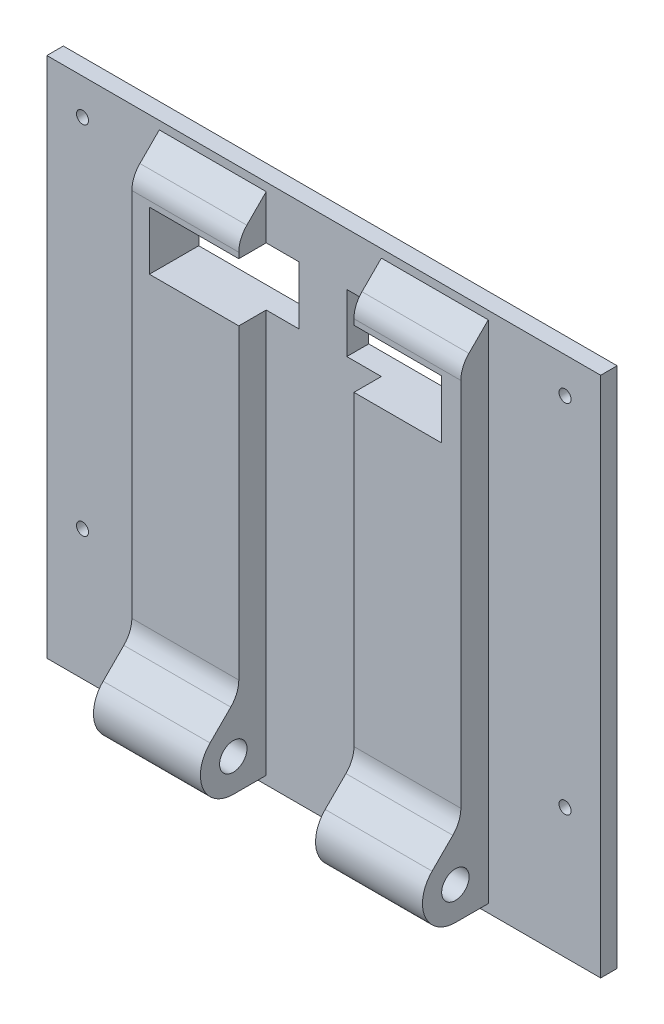
SolidWorks part; units mm, degrees
ref_plane "Front Plane" through (0, 0, 0) normal (0, 0, 1) x (1, 0, 0)
ref_plane "Top Plane" through (0, 0, 0) normal (0, 1, 0) x (1, 0, 0)
ref_plane "Right Plane" through (0, 0, 0) normal (1, 0, 0) x (0, 0, -1)
sketch "Sketch1" plane through (0, 0, 0) normal (0, 0, 1) x (1, 0, 0)
  line L1 (0, 43.6) -> (0, 0) construction
  line L2 (0, 0) -> (0, -43.6) construction
  line L3 (-46.5, 0) -> (0, 0) construction
  line L4 (0, 0) -> (46.5, 0) construction
  line L5 (46.5, 43.6) -> (46.5, -43.6) construction
  line L6 (-44, 41.1) -> (-44, -23.9) construction
  line L7 (-44, -23.9) -> (44, -23.9) construction
  line L8 (44, -23.9) -> (44, 41.1) construction
  line L9 (44, 41.1) -> (-44, 41.1) construction
  line L10 (50.5, 47.6) -> (-50.5, 47.6)
  line L11 (50.5, 47.6) -> (50.5, -47.6)
  line L12 (50.5, -47.6) -> (-50.5, -47.6)
  line L13 (-50.5, 47.6) -> (-50.5, -47.6)
  line L16 (49, -4.7) -> (49, 21.4) construction
  line L17 (49, 21.4) -> (46.5, 21.4) construction
  line L18 (46.5, 21.4) -> (46.5, 43.6) construction
  line L19 (46.5, 43.6) -> (-46.5, 43.6) construction
  line L20 (-46.5, 43.6) -> (-46.5, -43.6) construction
  line L21 (-46.5, -43.6) -> (46.5, -43.6) construction
  line L22 (46.5, -43.6) -> (46.5, -4.7) construction
  line L23 (46.5, -4.7) -> (49, -4.7) construction
  line L25 (-26.8, 38) -> (-26.8, 27.4)
  line L26 (-4.5, 38) -> (-26.8, 38)
  line L27 (-4.5, 27.4) -> (-4.5, 38)
  line L28 (-26.8, 27.4) -> (-4.5, 27.4)
  line L33 (4.2, 38) -> (4.2, 27.4)
  line L34 (26.5, 38) -> (4.2, 38)
  line L35 (26.5, 27.4) -> (26.5, 38)
  line L36 (4.2, 27.4) -> (26.5, 27.4)
  circle A4 centre (44, 41.1) radius 1.1
  circle A5 centre (44, -23.9) radius 1.1
  circle A6 centre (-44, 41.1) radius 1.1
  circle A7 centre (-44, -23.9) radius 1.1
  point P36 (-4.5, 32.7)
  dimension "D11" = 2.2
  dimension "D1" = 87.2
  dimension "D2" = 93
  dimension "D3" = 2.5
  dimension "D4" = 38.9
  dimension "D5" = 26.1
  dimension "D6" = 10.6
  dimension "D7" = 5.6
  dimension "D8" = 4.5
  dimension "D9" = 4.2
  dimension "D10" = 22.3
  dimension "D12" = 2.5
  dimension "D13" = 65
  dimension "D14" = 88
  dimension "D15" = 2.5
  dimension "D16" = 50.5
  dimension "D17" = 101
  dimension "D18" = 95.2
  dimension "D19" = 47.6
extrude "Boss-Extrude1" add sketch "Sketch1" along normal blind 3
sketch "Sketch2" [suppressed] plane through (0, 0, 3) normal (0, 0, 1) x (1, 0, 0)
  line L0 (46.5, 46.1) -> (-46.5, 46.1)
  line L1 (-49, 43.6) -> (-49, -43.6)
  line L2 (-46.5, -46.1) -> (46.5, -46.1)
  line L3 (49, -43.6) -> (49, -7.2)
  line L7 (49, 23.9) -> (49, 43.6)
  line L8 (50.5, -47.6) -> (50.5, 47.6) construction
  line L9 (-50.5, -47.6) -> (50.5, -47.6) construction
  line L16 (46.5, -4.7) -> (49, -4.7)
  line L18 (49, 21.4) -> (46.5, 21.4)
  line L19 (46.5, 21.4) -> (46.5, 43.6)
  line L20 (46.5, 43.6) -> (-46.5, 43.6)
  line L21 (-46.5, 43.6) -> (-46.5, -43.6)
  line L22 (-46.5, -43.6) -> (46.5, -43.6)
  line L23 (46.5, -43.6) -> (46.5, -4.7)
  line L24 (-49, -46.1) -> (49, -46.1) construction
  line L25 (49, -46.1) -> (49, -7.2) construction
  line L26 (-49, 46.1) -> (-49, -46.1) construction
  line L27 (49, 23.9) -> (49, 46.1) construction
  line L28 (49, 46.1) -> (-49, 46.1) construction
  line L29 (49, 23.9) -> (49, 21.4)
  line L30 (49, -4.7) -> (49, -7.2)
  line L31 (51.5, 23.9) -> (49, 23.9) construction
  line L32 (51.5, -7.2) -> (51.5, 23.9) construction
  line L33 (49, -7.2) -> (51.5, -7.2) construction
  line L41 (49, -4.7) -> (49, 21.4) construction
  arc A0 (46.5, -46.1) -> (49, -43.6) centre (46.5, -43.6) ccw
  arc A1 (-49, -43.6) -> (-46.5, -46.1) centre (-46.5, -43.6) ccw
  arc A2 (49, 43.6) -> (46.5, 46.1) centre (46.5, 43.6) ccw
  arc A3 (-49, 43.6) -> (-46.5, 46.1) centre (-46.5, 43.6) cw
  dimension "D3" = 2.5
  dimension "D1" = 97
  dimension "D2" = 87.2
  dimension "D4" = 4
sketch "Sketch4" plane through (0, 0, 3) normal (0, 0, 1) x (1, 0, 0)
  line L0 (0, 46.1) -> (0, -46.1) construction
  line L3 (50.5, 47.6) -> (-50.5, 47.6) construction
  line L5 (-50.5, -47.6) -> (50.5, -47.6) construction
  line L6 (-50.5, 47.6) -> (-50.5, -47.6) construction
  point P8 (0, 0)
  dimension "D1" = 1.5
  dimension "D2" = 1.5
  dimension "D3" = 50.5
ref_plane "Plane1" through (0, 0, 0) normal (-1, 0, 0) x (0, -1, 0)
sketch "Sketch5" plane through (0, 0, 0) normal (-1, 0, 0) x (0, -1, 0)
  line L0 (-46.1, 3) -> (46.1, 3) construction
  line L1 (46.1, 9) -> (46.1, 3) construction
  line L2 (46.1, 9) -> (46.1, 3)
  line L3 (46.1, 3) -> (25.6147, 3)
  line L4 (32.0792, 9.4645) -> (35.8574, 13.2426)
  line L5 (25.6147, 3) -> (-46.1, 3)
  line L6 (-46.1, 3) -> (-42.5645, 6.5355)
  line L7 (-39.0289, 8) -> (28.5437, 8)
  line L8 (25.6147, 3) -> (30.6147, 8) construction
  line L10 (47.6, 3) -> (47.6, 0) construction
  circle A2 centre (40.1, 9) radius 2.5
  arc A3 (46.1, 9) -> (35.8574, 13.2426) centre (40.1, 9) ccw
  arc A4 (28.5437, 8) -> (32.0792, 9.4645) centre (28.5437, 13) ccw
  arc A5 (-42.5645, 6.5355) -> (-39.0289, 8) centre (-39.0289, 3) cw
  arc A6 (35.8574, 13.2426) -> (40.1, 3) centre (40.1, 9) ccw construction
  arc A7 (40.1, 3) -> (46.1, 9) centre (40.1, 9) ccw construction
  dimension "D1" = 5
  dimension "D2" = 12
  dimension "D5" = 5
  dimension "D3" = 45
  dimension "D4" = 5
  dimension "D6" = 1.5
  dimension "D7" = 1.5
  dimension "D8" = 20.4853
extrude "Boss-Extrude3" add sketch "Sketch5" along normal blind 30 and the other way blind 30
sketch "Sketch7" plane through (-30, 0, 0) normal (-1, 0, 0) x (0, 0, 1)
  line L6 (3, 46.1) -> (3, -46.1)
  line L7 (3, 46.1) -> (3, -46.1)
  line L8 (13.2426, -35.8574) -> (9.4645, -32.0792)
  line L9 (8, -28.5437) -> (8, 39.0289)
  line L15 (6.5355, 42.5645) -> (3, 46.1)
  line L17 (3, -46.1) -> (9, -46.1)
  line L18 (13.2426, -35.8574) -> (9.4645, -32.0792)
  line L19 (8, -28.5437) -> (8, 39.0289)
  line L20 (6.5355, 42.5645) -> (3, 46.1)
  line L22 (3, -46.1) -> (9, -46.1)
  arc A3 (9, -46.1) -> (13.2426, -35.8574) centre (9, -40.1) ccw
  arc A4 (8, -28.5437) -> (9.4645, -32.0792) centre (13, -28.5437) ccw
  arc A5 (8, 39.0289) -> (6.5355, 42.5645) centre (3, 39.0289) ccw
  arc A9 (9, -46.1) -> (13.2426, -35.8574) centre (9, -40.1) ccw
  arc A10 (8, -28.5437) -> (9.4645, -32.0792) centre (13, -28.5437) ccw
  arc A11 (8, 39.0289) -> (6.5355, 42.5645) centre (3, 39.0289) ccw
  dimension "D1" = 0
extrude "Cut-Extrude1" cut sketch "Sketch7" against normal blind 21 from offset 19.5 offset against normal yes
sketch "Sketch8" plane through (-30, 0, 0) normal (-1, 0, 0) x (0, 0, 1)
  line L0 (9.4645, -32.0792) -> (3, -25.6147)
  line L1 (13.2426, -35.8574) -> (9.4645, -32.0792) construction
  line L5 (13.2426, -35.8574) -> (9.4645, -32.0792)
  line L6 (8, -28.5437) -> (8, 39.0289)
  line L7 (6.5355, 42.5645) -> (3, 46.1)
  line L8 (3, 46.1) -> (3, -46.1)
  line L9 (3, -46.1) -> (9, -46.1)
  line L11 (8, -28.5437) -> (8, 39.0289)
  line L12 (6.5355, 42.5645) -> (3, 46.1)
  line L16 (3, 46.1) -> (3, -46.1)
  arc A3 (9, -46.1) -> (13.2426, -35.8574) centre (9, -40.1) ccw
  arc A4 (8, -28.5437) -> (9.4645, -32.0792) centre (13, -28.5437) ccw
  arc A5 (8, 39.0289) -> (6.5355, 42.5645) centre (3, 39.0289) ccw
  arc A7 (8, -28.5437) -> (9.4645, -32.0792) centre (13, -28.5437) ccw
  arc A8 (8, 39.0289) -> (6.5355, 42.5645) centre (3, 39.0289) ccw
  dimension "D1" = 0
sketch "Sketch9" plane through (0, 0, 3) normal (0, 0, 1) x (1, 0, 0)
  line L0 (4.2, 38) -> (4.2, 27.4) construction
  line L1 (26.5, 38) -> (4.2, 38) construction
  line L2 (26.5, 27.4) -> (26.5, 38) construction
  line L3 (4.2, 27.4) -> (26.5, 27.4) construction
  line L4 (4.2, 38) -> (4.2, 27.4)
  line L5 (26.5, 38) -> (4.2, 38)
  line L6 (26.5, 27.4) -> (26.5, 38)
  line L7 (4.2, 27.4) -> (26.5, 27.4)
  line L8 (-26.8, 38) -> (-26.8, 27.4) construction
  line L9 (-4.5, 38) -> (-26.8, 38) construction
  line L10 (-4.5, 27.4) -> (-4.5, 38) construction
  line L11 (-26.8, 27.4) -> (-4.5, 27.4) construction
  line L12 (-26.8, 38) -> (-26.8, 27.4)
  line L13 (-4.5, 38) -> (-26.8, 38)
  line L14 (-4.5, 27.4) -> (-4.5, 38)
  line L15 (-26.8, 27.4) -> (-4.5, 27.4)
extrude "Cut-Extrude4" cut sketch "Sketch9" along normal blind 10
sketch "Sketch10" plane through (0, 0, 0) normal (0, 0, -1) x (-1, 0, 0)
  line L0 (-50.5, -47.6) -> (-50.5, 47.6) construction
  line L1 (-47.5, 44.6) -> (47.5, 44.6)
  line L2 (-47.5, 44.6) -> (-47.5, -44.6)
  line L3 (-47.5, -44.6) -> (47.5, -44.6)
  line L4 (47.5, 44.6) -> (47.5, -44.6)
  line L5 (50.5, -47.6) -> (-50.5, -47.6) construction
  dimension "D1" = 3
  dimension "D2" = 95
  dimension "D3" = 3
  dimension "D4" = 89.2
extrude "Boss-Extrude4" add sketch "Sketch10" along normal blind 1
sketch "Sketch11" plane through (0, 0, 0) normal (0, 0, 1) x (1, 0, 0)
  line L0 (26.5, 38) -> (4.2, 38) construction
  line L1 (4.2, 38) -> (4.2, 27.4) construction
  line L2 (4.2, 27.4) -> (26.5, 27.4) construction
  line L3 (26.5, 27.4) -> (26.5, 38) construction
  line L4 (-4.5, 38) -> (-26.8, 38) construction
  line L5 (-26.8, 38) -> (-26.8, 27.4) construction
  line L6 (-26.8, 27.4) -> (-4.5, 27.4) construction
  line L7 (-4.5, 27.4) -> (-4.5, 38) construction
  line L8 (26.5, 38) -> (4.2, 38)
  line L9 (4.2, 38) -> (4.2, 27.4)
  line L10 (4.2, 27.4) -> (26.5, 27.4)
  line L11 (26.5, 27.4) -> (26.5, 38)
  line L12 (-4.5, 38) -> (-26.8, 38)
  line L13 (-26.8, 38) -> (-26.8, 27.4)
  line L14 (-26.8, 27.4) -> (-4.5, 27.4)
  line L15 (-4.5, 27.4) -> (-4.5, 38)
  circle A0 centre (-44, 41.1) radius 1.1 construction
  circle A1 centre (-44, -23.9) radius 1.1 construction
  circle A2 centre (44, -23.9) radius 1.1 construction
  circle A3 centre (44, 41.1) radius 1.1 construction
  circle A4 centre (-44, 41.1) radius 1.1
  circle A5 centre (-44, -23.9) radius 1.1
  circle A6 centre (44, -23.9) radius 1.1
  circle A7 centre (44, 41.1) radius 1.1
extrude "Cut-Extrude5" cut sketch "Sketch11" against normal blind 1.2
